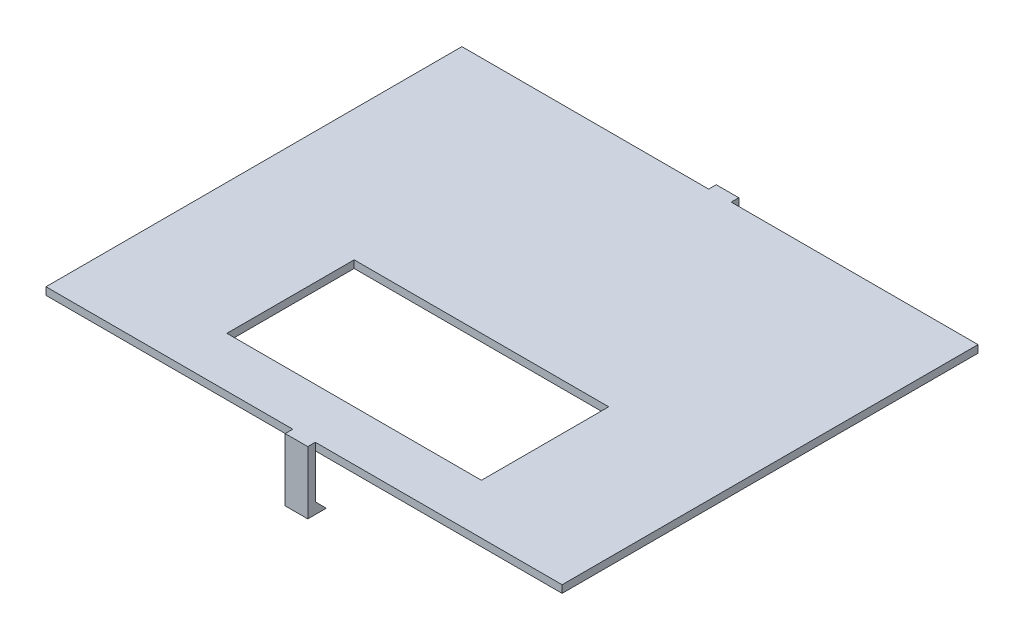
SolidWorks part; units mm, degrees
ref_plane "Front Plane" through (0, 0, 0) normal (0, 0, 1) x (1, 0, 0)
ref_plane "Top Plane" through (0, 0, 0) normal (0, 1, 0) x (1, 0, 0)
ref_plane "Right Plane" through (0, 0, 0) normal (1, 0, 0) x (0, 0, -1)
sketch "Sketch1" plane through (0, 0, 0) normal (0, 1, 0) x (1, 0, 0)
  line L1 (-33.2077, 29.4085) -> (69.7923, 29.4085)
  line L2 (-33.2077, 29.4085) -> (-33.2077, -53.5915)
  line L3 (-33.2077, -53.5915) -> (69.7923, -53.5915)
  line L4 (69.7923, 29.4085) -> (69.7923, -53.5915)
  dimension "D1" = 103
  dimension "D2" = 83
extrude "Boss-Extrude1" add sketch "Sketch1" along normal blind 1.5
ref_plane "Plane1" through (18.2923, 0, 0) normal (1, 0, 0) x (0, 0, -1)
sketch "Sketch2" plane through (18.2923, 0, 0) normal (1, 0, 0) x (0, 0, -1)
  line L2 (-53.5915, 1.5) -> (-55.1015, 1.5)
  line L3 (-55.1015, 1.5) -> (-55.1015, -11)
  line L4 (-55.1015, -11) -> (-51.3954, -11)
  line L5 (-51.3954, -11) -> (-53.6015, -8.7938)
  line L8 (-53.6015, -8.7938) -> (-53.6015, 0)
  line L9 (-12.0915, 0) -> (-12.0915, -22.2544) construction
  line L10 (-53.5915, 0) -> (29.4085, 0) construction
  line L11 (-53.6015, 0) -> (-53.5915, 0)
  line L12 (-53.5915, 0) -> (-53.5915, 1.5)
  line L13 (29.4085, 0) -> (29.4085, 1.5)
  line L14 (29.4185, 0) -> (29.4085, 0)
  line L15 (29.4185, -8.7938) -> (29.4185, 0)
  line L16 (27.2123, -11) -> (29.4185, -8.7938)
  line L17 (30.9185, -11) -> (27.2123, -11)
  line L18 (30.9185, 1.5) -> (30.9185, -11)
  line L19 (29.4085, 1.5) -> (30.9185, 1.5)
  dimension "D1" = 11
  dimension "D2" = 3.12
  dimension "D3" = 45
  dimension "D4" = 1.5
  dimension "D5" = 0.01
extrude "Boss-Extrude2" add sketch "Sketch2" along normal mid plane 4.5
sketch "Sketch3" plane through (0, 1.5, 0) normal (0, 1, 0) x (1, 0, 0)
  line L0 (18.2923, -55.6905) -> (18.2923, 30.9185) construction
  line L1 (-7.1077, -18.1915) -> (43.6923, -18.1915)
  line L2 (-7.1077, -18.1915) -> (-7.1077, -43.5915)
  line L3 (-7.1077, -43.5915) -> (43.6923, -43.5915)
  line L4 (43.6923, -18.1915) -> (43.6923, -43.5915)
  line L5 (18.2923, -11.8799) -> (18.2923, 11.8799) construction
  line L6 (20.5423, 30.9185) -> (16.0423, 30.9185) construction
  line L7 (-33.2077, -53.5915) -> (16.0423, -53.5915) construction
  line L8 (-33.2077, -12.0915) -> (69.7923, -12.0915) construction
  line L9 (-33.2077, 29.4085) -> (-33.2077, -53.5915) construction
  line L10 (69.7923, -53.5915) -> (69.7923, 29.4085) construction
  dimension "D1" = 25.4
  dimension "D2" = 50.8
  dimension "D3" = 35.4
  dimension "D4" = 25.4
extrude "Cut-Extrude1" cut sketch "Sketch3" against normal blind 1.5
